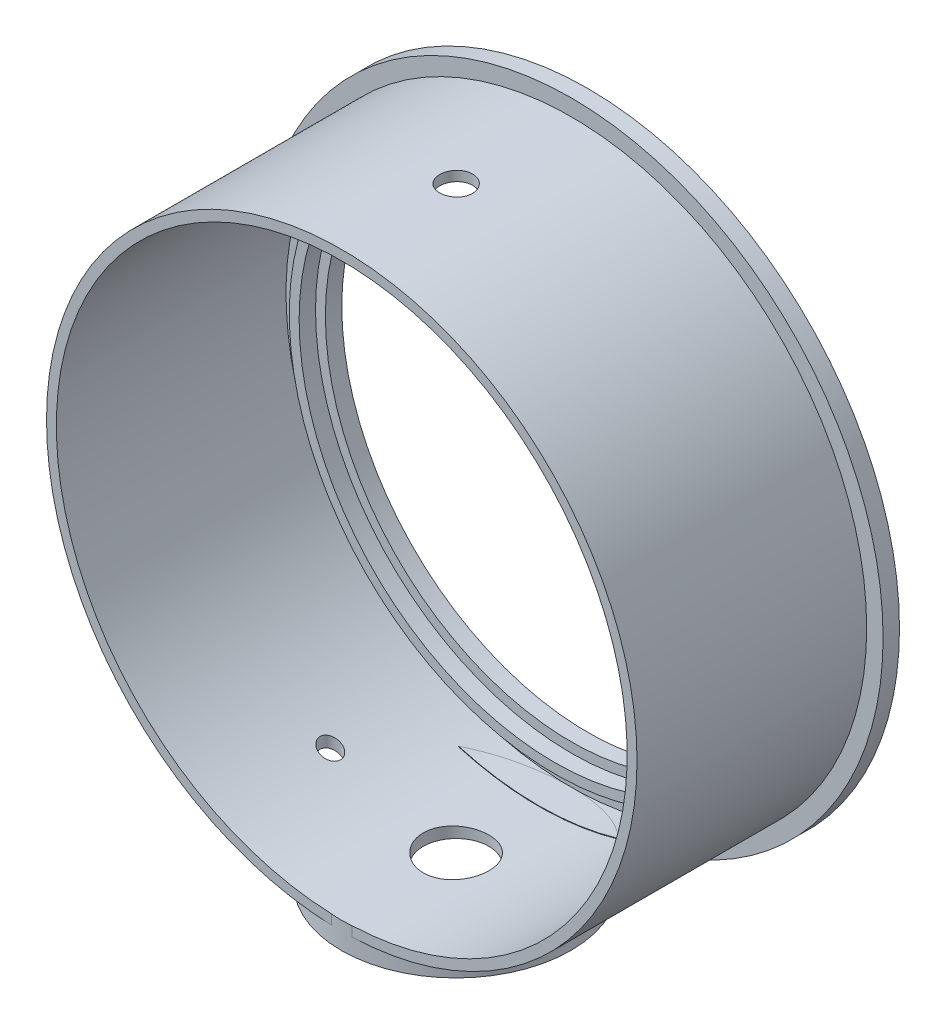
SolidWorks part; units mm, degrees
ref_plane "Front Plane" through (0, 0, 0) normal (0, 0, 1) x (1, 0, 0)
ref_plane "Top Plane" through (0, 0, 0) normal (0, 1, 0) x (1, 0, 0)
ref_plane "Right Plane" through (0, 0, 0) normal (1, 0, 0) x (0, 0, -1)
sketch "Sketch2" plane through (0, 0, 0) normal (0, 0, 1) x (1, 0, 0)
  circle A0 centre (0, 0) radius 95
  circle A1 centre (0, 0) radius 75
  dimension "D1" = 190
  dimension "D2" = 20
extrude "Boss-Extrude1" add sketch "Sketch2" along normal blind 5
sketch "Sketch3" plane through (0, 0, 0) normal (0, 0, 1) x (1, 0, 0)
  circle A0 centre (0, 0) radius 90
  circle A1 centre (0, 0) radius 95 construction
  circle A2 centre (0, 0) radius 87
  dimension "D1" = 5
  dimension "D2" = 3
extrude "Boss-Extrude2" add sketch "Sketch3" along normal blind 75
sketch "Sketch4" plane through (0, 0, 0) normal (0, 0, 1) x (1, 0, 0)
  circle A0 centre (0, 0) radius 78
  circle A1 centre (0, 0) radius 75 construction
  circle A2 centre (0, 0) radius 81
  dimension "D1" = 3
  dimension "D2" = 3
extrude "Boss-Extrude4" add sketch "Sketch4" along normal blind 10 contours A0 | A2
sketch "Sketch6" plane through (0, 0, 0) normal (0, 1, 0) x (1, 0, 0)
  circle A0 centre (0, -40.1438) radius 35
  dimension "D1" = 70
extrude "Boss-Extrude5" add sketch "Sketch6" against normal blind 95
sketch "Sketch7" plane through (0, 0, 0) normal (0, 0, 1) x (1, 0, 0)
  circle A0 centre (0, 0) radius 75
extrude "Cut-Extrude1" cut sketch "Sketch7" along normal blind 95
ref_plane "Plane1" through (0, 0, 15) normal (0, 0, 1) x (1, 0, 0)
sketch "Sketch8" plane through (0, 0, 15) normal (0, 0, 1) x (1, 0, 0)
  circle A0 centre (0, 0) radius 87
  circle A1 centre (0, 0) radius 87
  circle A2 centre (0, 0) radius 87
extrude "Cut-Extrude3" cut sketch "Sketch8" along normal blind 95 contours A0
sketch "Sketch9" plane through (0, 0, 15) normal (0, 0, 1) x (1, 0, 0)
  circle A0 centre (0, 0) radius 86.8274
extrude "Cut-Extrude4" cut sketch "Sketch9" against normal blind 10
sketch "Sketch10" plane through (0, 0, 0) normal (0, 0, 1) x (1, 0, 0)
  circle A0 centre (0, 0) radius 78
  circle A1 centre (0, 0) radius 75 construction
  circle A2 centre (0, 0) radius 81
  dimension "D1" = 3
  dimension "D2" = 3
extrude "Boss-Extrude6" add sketch "Sketch10" along normal blind 10 contours A2 | A0
sketch "Sketch11" plane through (0, -95, 0) normal (0, -1, 0) x (1, 0, 0)
  circle A0 centre (0, 40.1438) radius 32
  dimension "D1" = 64
extrude "Cut-Extrude5" cut sketch "Sketch11" against normal blind 5 contours A0
sketch "Sketch12" plane through (0, -90, 0) normal (0, -1, 0) x (1, 0, 0)
  circle A0 centre (0, 40.1438) radius 10
  dimension "D1" = 20
extrude "Cut-Extrude6" cut sketch "Sketch12" against normal blind 5 contours A0
sketch "Sketch13" plane through (0, -90, 0) normal (0, -1, 0) x (1, 0, 0)
  circle A0 centre (0, 40.1438) radius 5
  dimension "D1" = 10
extrude "Cut-Extrude7" cut sketch "Sketch13" against normal blind 185 contours A0
sketch "Sketch14" plane through (0, 0, 0) normal (0, 1, 0) x (1, 0, 0)
  circle A0 centre (-38.2, -40.2985) radius 3.1161
  circle A2 centre (0, -40.1438) radius 35 construction
  dimension "D1" = 38.2
extrude "Cut-Extrude9" cut sketch "Sketch14" against normal blind 185
